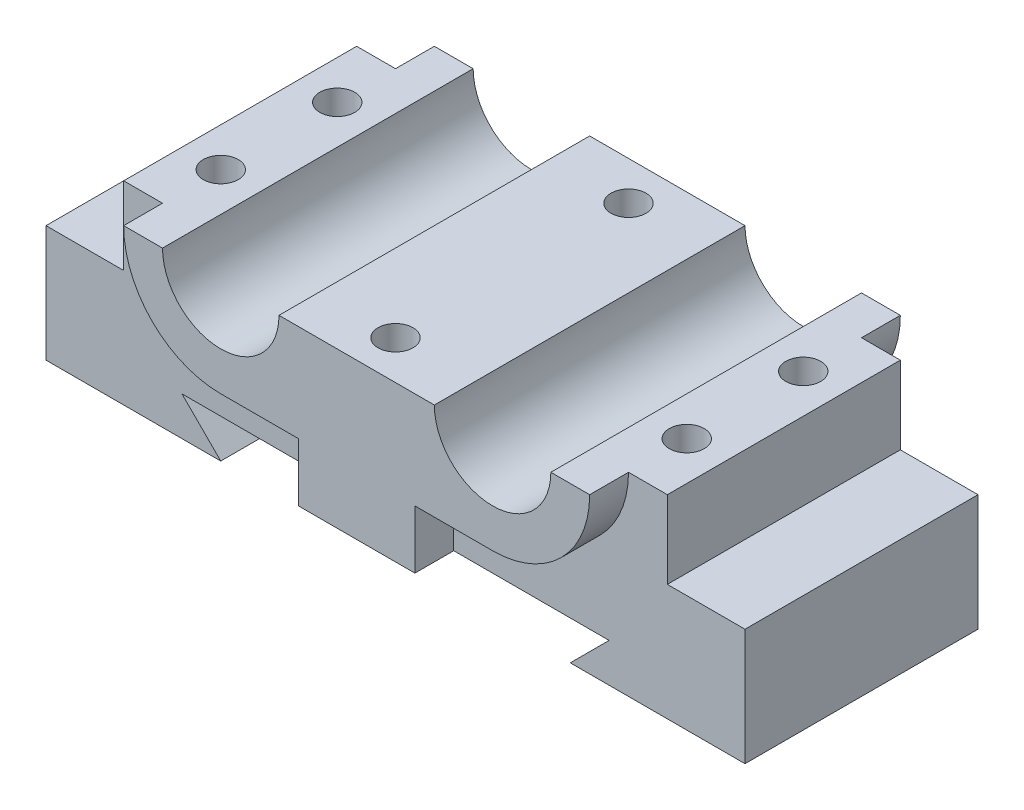
SolidWorks part; units mm, degrees
ref_plane "Front Plane" through (0, 0, 0) normal (0, 0, 1) x (1, 0, 0)
ref_plane "Top Plane" through (0, 0, 0) normal (0, 1, 0) x (1, 0, 0)
ref_plane "Right Plane" through (0, 0, 0) normal (1, 0, 0) x (0, 0, -1)
sketch "Sketch1" plane through (0, 0, 0) normal (0, 1, 0) x (1, 0, 0)
  line L1 (-45, -20) -> (45, -20)
  line L2 (-45, -20) -> (-45, 20)
  line L3 (-45, 20) -> (45, 20)
  line L4 (45, -20) -> (45, 20)
  line L5 (-45, -20) -> (45, 20) construction
  line L6 (-45, 20) -> (45, -20) construction
  point P0 (0, 0)
  dimension "D1" = 40
  dimension "D2" = 90
extrude "Boss-Extrude1" add sketch "Sketch1" along normal blind 25
sketch "Sketch2" plane through (0, 0, 20) normal (0, 0, 1) x (1, 0, 0)
  line L0 (-45, 25) -> (45, 25) construction
  line L5 (0, 0) -> (0, 13.0594) construction
  line L6 (45, 25) -> (35, 25)
  line L7 (45, 25) -> (45, 15)
  line L8 (45, 15) -> (35, 15)
  line L9 (35, 25) -> (35, 15)
  line L10 (-45, 0) -> (45, 0) construction
  line L11 (-45, 15) -> (-35, 15)
  line L12 (-35, 25) -> (-35, 15)
  line L13 (-45, 25) -> (-35, 25)
  line L14 (-45, 25) -> (-45, 15)
  circle A0 centre (-17.5, 25) radius 7.5
  circle A1 centre (17.5, 25) radius 7.5
  dimension "D1" = 15
  dimension "D2" = 17.5
  dimension "D3" = 17.5
  dimension "D4" = 10
  dimension "D5" = 10
extrude "Cut-Extrude1" cut sketch "Sketch2" against normal up to next
sketch "Sketch3" plane through (0, 0, 20) normal (0, 0, 1) x (1, 0, 0)
  line L0 (-35, 25) -> (-25, 25) construction
  line L1 (-7.5, 12.5) -> (-7.5, 0)
  line L2 (-45, 0) -> (45, 0) construction
  line L3 (-7.5, 12.5) -> (-17.5, 12.5)
  line L4 (0, 0) -> (0, 17.3483) construction
  line L5 (7.5, 12.5) -> (7.5, 0)
  line L6 (7.5, 12.5) -> (17.5, 12.5)
  line L7 (-30, 25) -> (-45, 25)
  line L8 (-45, 25) -> (-45, 0)
  line L9 (-45, 0) -> (-7.5, 0)
  line L10 (-45, 15) -> (-45, 0) construction
  line L11 (45, 0) -> (7.5, 0)
  line L12 (45, 25) -> (45, 0)
  line L13 (30, 25) -> (45, 25)
  arc A0 (-30, 25) -> (-17.5, 12.5) centre (-17.5, 25) ccw
  arc A1 (-25, 25) -> (-10, 25) centre (-17.5, 25) ccw construction
  arc A2 (30, 25) -> (17.5, 12.5) centre (17.5, 25) cw
  dimension "D1" = 12.5
  dimension "D2" = 7.5
extrude "Cut-Extrude2" cut sketch "Sketch3" against normal blind 5
mirror "Mirror1" about plane through (0, 0, 0) normal (0, 0, 1) of "Cut-Extrude2"
sketch "Sketch4" plane through (0, 0, 20) normal (0, 0, 1) x (1, 0, 0)
  line L0 (-27.5, 5) -> (27.5, 5)
  line L1 (27.5, 5) -> (22.5, 0)
  line L2 (7.5, 0) -> (45, 0) construction
  line L3 (0, 0) -> (0, 11.3812) construction
  line L4 (-7.5, 0) -> (7.5, 0) construction
  line L5 (-27.5, 5) -> (-22.5, 0)
  line L6 (45, 0) -> (45, 15) construction
  line L7 (-22.5, 0) -> (22.5, 0)
  dimension "D1" = 5
  dimension "D2" = 5
  dimension "D3" = 22.5
extrude "Cut-Extrude3" cut sketch "Sketch4" against normal through all
sketch "Sketch5" plane through (0, 25, 0) normal (0, 1, 0) x (1, 0, 0)
  line L0 (-30, -20) -> (-25, -20) construction
  line L1 (-25, 20) -> (-30, 20) construction
  line L3 (35, 15) -> (30, 15) construction
  line L4 (35, -15) -> (45, -15) construction
  line L5 (0, 0) -> (0, 8.4845) construction
  circle A0 centre (-30, 7.5) radius 2.25
  circle A1 centre (-30, -7.5) radius 2.25
  circle A2 centre (0, 15) radius 2.25
  circle A3 centre (0, -15) radius 2.25
  circle A4 centre (30, 7.5) radius 2.25
  circle A5 centre (30, -7.5) radius 2.25
  dimension "D1" = 4.5
  dimension "D2" = 12.5
  dimension "D3" = 12.5
  dimension "D4" = 30
  dimension "D5" = 30
  dimension "D6" = 30
extrude "Cut-Extrude4" cut sketch "Sketch5" against normal blind 15
